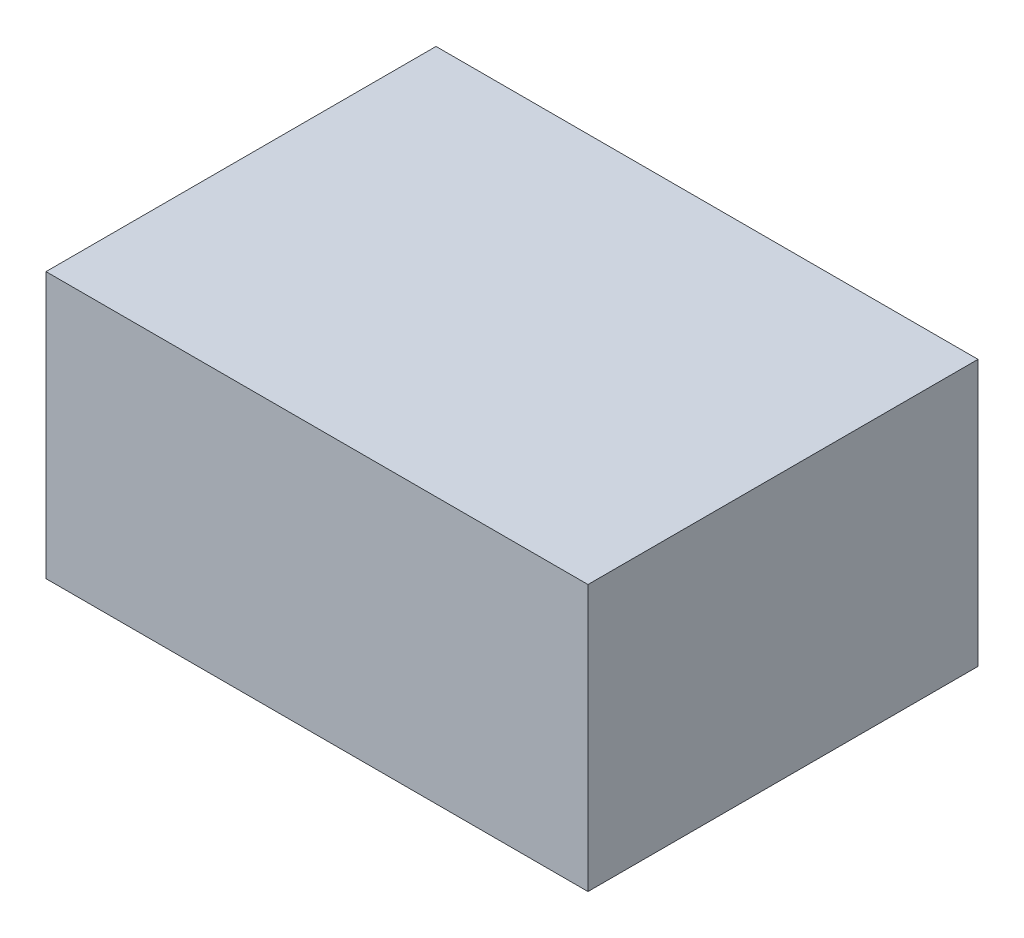
SolidWorks part; units mm, degrees
ref_plane "前视基准面" through (0, 0, 0) normal (0, 0, 1) x (1, 0, 0)
ref_plane "上视基准面" through (0, 0, 0) normal (0, 1, 0) x (1, 0, 0)
ref_plane "右视基准面" through (0, 0, 0) normal (1, 0, 0) x (0, 0, -1)
other "Configuration Table"
sketch "草图1" plane through (0, 0, 0) normal (0, 1, 0) x (1, 0, 0)
  line L1 (-42.8, -30.8) -> (42.8, -30.8)
  line L2 (-42.8, -30.8) -> (-42.8, 30.8)
  line L3 (-42.8, 30.8) -> (42.8, 30.8)
  line L4 (42.8, -30.8) -> (42.8, 30.8)
  line L5 (-42.8, -30.8) -> (42.8, 30.8) construction
  line L6 (-42.8, 30.8) -> (42.8, -30.8) construction
  point P1 (0, 0)
  dimension "D1" = 85.6
  dimension "D2" = 61.6
extrude "凸台-拉伸1" add sketch "草图1" along normal blind 42
